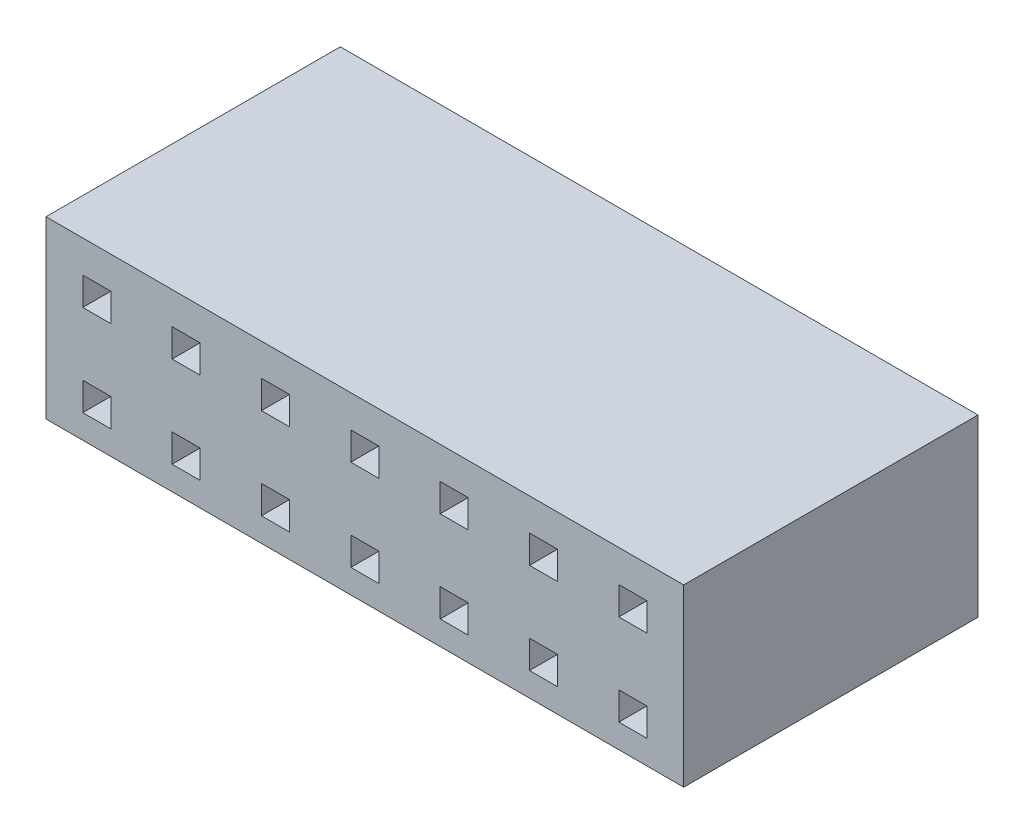
SolidWorks part; units mm, degrees
ref_plane "Přední rovina" through (0, 0, 0) normal (0, 0, 1) x (1, 0, 0)
ref_plane "Horní rovina" through (0, 0, 0) normal (0, 1, 0) x (1, 0, 0)
ref_plane "Pravá rovina" through (0, 0, 0) normal (1, 0, 0) x (0, 0, -1)
sketch "Skica1" plane through (0, 0, 0) normal (0, 0, 1) x (1, 0, 0)
  line L1 (0, 0) -> (18.2, 0)
  line L2 (0, 0) -> (0, 5)
  line L3 (0, 5) -> (18.2, 5)
  line L4 (18.2, 0) -> (18.2, 5)
  dimension "D1" = 18.2
  dimension "D2" = 5
extrude "Přidat vysunutím1" add sketch "Skica1" along normal blind 8.4
sketch "Skica3" plane through (0, 0, 8.4) normal (0, 0, 1) x (1, 0, 0)
  line L1 (1.05, 4.0827) -> (1.85, 4.0827)
  line L2 (1.05, 4.0827) -> (1.05, 3.2827)
  line L3 (1.05, 3.2827) -> (1.85, 3.2827)
  line L4 (1.85, 4.0827) -> (1.85, 3.2827)
  line L5 (1.05, 1.4827) -> (1.85, 1.4827)
  line L6 (1.05, 1.4827) -> (1.05, 0.6827)
  line L7 (1.05, 0.6827) -> (1.85, 0.6827)
  line L8 (1.85, 1.4827) -> (1.85, 0.6827)
  line L9 (6.15, 4.0827) -> (6.95, 4.0827)
  line L10 (0, 5) -> (0, 0) construction
  line L12 (3.6, 4.0827) -> (4.4, 4.0827)
  line L13 (3.6, 4.0827) -> (3.6, 3.2827)
  line L14 (3.6, 3.2827) -> (4.4, 3.2827)
  line L15 (4.4, 4.0827) -> (4.4, 3.2827)
  line L16 (3.6, 1.4827) -> (4.4, 1.4827)
  line L17 (3.6, 1.4827) -> (3.6, 0.6827)
  line L18 (3.6, 0.6827) -> (4.4, 0.6827)
  line L19 (4.4, 1.4827) -> (4.4, 0.6827)
  line L20 (6.15, 4.0827) -> (6.15, 3.2827)
  line L21 (6.15, 3.2827) -> (6.95, 3.2827)
  line L22 (6.95, 4.0827) -> (6.95, 3.2827)
  line L23 (6.15, 1.4827) -> (6.95, 1.4827)
  line L24 (6.15, 1.4827) -> (6.15, 0.6827)
  line L25 (6.15, 0.6827) -> (6.95, 0.6827)
  line L26 (6.95, 1.4827) -> (6.95, 0.6827)
  line L27 (8.7, 4.0827) -> (9.5, 4.0827)
  line L28 (8.7, 4.0827) -> (8.7, 3.2827)
  line L29 (8.7, 3.2827) -> (9.5, 3.2827)
  line L30 (9.5, 4.0827) -> (9.5, 3.2827)
  line L31 (8.7, 1.4827) -> (9.5, 1.4827)
  line L32 (8.7, 1.4827) -> (8.7, 0.6827)
  line L33 (8.7, 0.6827) -> (9.5, 0.6827)
  line L34 (9.5, 1.4827) -> (9.5, 0.6827)
  line L35 (11.25, 4.0827) -> (12.05, 4.0827)
  line L36 (11.25, 4.0827) -> (11.25, 3.2827)
  line L37 (11.25, 3.2827) -> (12.05, 3.2827)
  line L38 (12.05, 4.0827) -> (12.05, 3.2827)
  line L39 (11.25, 1.4827) -> (12.05, 1.4827)
  line L40 (11.25, 1.4827) -> (11.25, 0.6827)
  line L41 (11.25, 0.6827) -> (12.05, 0.6827)
  line L42 (12.05, 1.4827) -> (12.05, 0.6827)
  line L43 (13.8, 4.0827) -> (14.6, 4.0827)
  line L44 (13.8, 4.0827) -> (13.8, 3.2827)
  line L45 (13.8, 3.2827) -> (14.6, 3.2827)
  line L46 (14.6, 4.0827) -> (14.6, 3.2827)
  line L47 (13.8, 1.4827) -> (14.6, 1.4827)
  line L48 (13.8, 1.4827) -> (13.8, 0.6827)
  line L49 (13.8, 0.6827) -> (14.6, 0.6827)
  line L50 (14.6, 1.4827) -> (14.6, 0.6827)
  line L51 (16.35, 4.0827) -> (17.15, 4.0827)
  line L52 (16.35, 4.0827) -> (16.35, 3.2827)
  line L53 (16.35, 3.2827) -> (17.15, 3.2827)
  line L54 (17.15, 4.0827) -> (17.15, 3.2827)
  line L55 (16.35, 1.4827) -> (17.15, 1.4827)
  line L56 (16.35, 1.4827) -> (16.35, 0.6827)
  line L57 (16.35, 0.6827) -> (17.15, 0.6827)
  line L58 (17.15, 1.4827) -> (17.15, 0.6827)
  dimension "D2" = 0.8
  dimension "D4" = 1.8
  dimension "D5" = 1.8
  dimension "D6" = 1.8
  dimension "D7" = 1.8
  dimension "D8" = 1.8
  dimension "D9" = 1.8
  dimension "D10" = 1.8
  dimension "D11" = 1.05
  dimension "D13" = 1.75
  dimension "D14" = 1.75
  dimension "D15" = 1.75
  dimension "D16" = 1.75
  dimension "D17" = 1.75
  dimension "D18" = 1.75
  dimension "D19" = 1.75
  dimension "D20" = 1.75
  dimension "D21" = 1.75
  dimension "D22" = 1.75
  dimension "D23" = 1.75
  dimension "D24" = 1.75
  dimension "D25" = 0.8
  dimension "D26" = 0.8
  dimension "D27" = 0.8
  dimension "D28" = 0.8
  dimension "D29" = 0.8
  dimension "D30" = 0.8
  dimension "D31" = 0.8
  dimension "D32" = 0.8
  dimension "D33" = 0.8
  dimension "D34" = 0.8
  dimension "D35" = 0.8
  dimension "D36" = 0.8
extrude "Odebrat vysunutím1" cut sketch "Skica3" against normal blind 6
ref_plane "Rovina1" through (9.1, 0, 0) normal (1, 0, 0) x (0, 0, -1)
